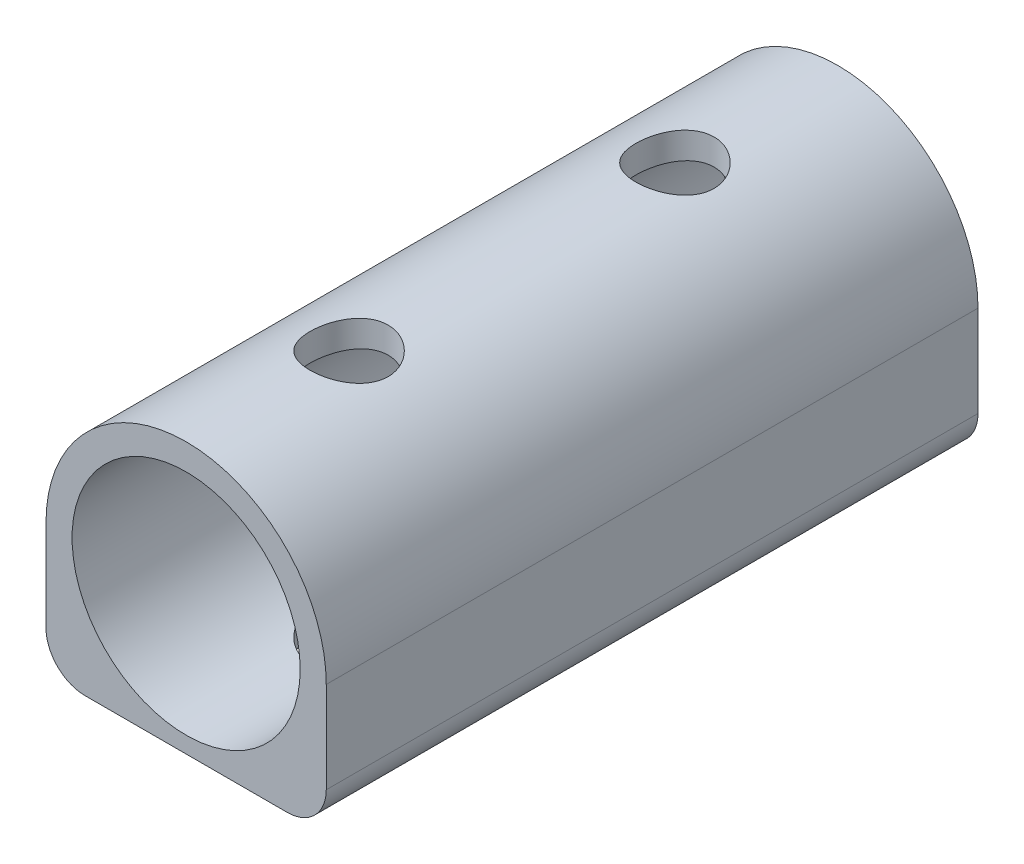
SolidWorks part; units mm, degrees
extrude "Base-Extrude" add sketch "Sketch1" along normal blind 100
sketch "Sketch1" plane through (0, 0, 0) normal (0, 0, 1) x (1, 0, 0)
  line L0 (-21.5, -20) -> (-21.5, 0)
  line L1 (21.5, 0) -> (21.5, -20)
  line L2 (21.5, -20) -> (-21.5, -20)
  arc A0 (-21.5, 0) -> (21.5, 0) centre (0, 0) cw
  dimension "D1" = 20
  dimension "Outer_D" = 43
ref_plane "Plane1" through (0, 0, 0) normal (0, 0, 1) x (1, 0, 0)
ref_plane "Plane2" through (0, 0, 0) normal (0, 1, 0) x (1, 0, 0)
ref_plane "Plane3" through (0, 0, 0) normal (1, 0, 0) x (0, 0, -1)
sketch "Sketch2" plane through (0, 0, 100) normal (0, 0, 1) x (1, 0, 0)
  circle A0 centre (0, 0) radius 17.5
extrude "Cut-Extrude1" cut sketch "Sketch2" against normal through all
sketch "Sketch3" plane through (0, -20, 0) normal (0, -1, 0) x (1, 0, 0)
  line L0 (21.5, 100) -> (-21.5, 100) construction
  line L3 (21.5, 100) -> (-21.5, 100) construction
  circle A0 centre (0, 25) radius 6
  circle A1 centre (0, 75) radius 6
  dimension "D2" = 12
extrude "Cut-Extrude2" cut sketch "Sketch3" against normal through all
fillet "Fillet1" radius 6 2 edges at (21.5, -20, 50) (-21.5, -20, 50)
equation "\"Hole1@Sketch3\" = \"Length@Base-Extrude\" / 4"
equation "\"Hole2@Sketch3\"= \"Length@Base-Extrude\" * 3 / 4"
equation "\"UpperWall\" = 4"
equation "\"Outer_D@Sketch1\" = \"Hole_Diameter@Sketch2\" + \"UpperWall\" * 2"
